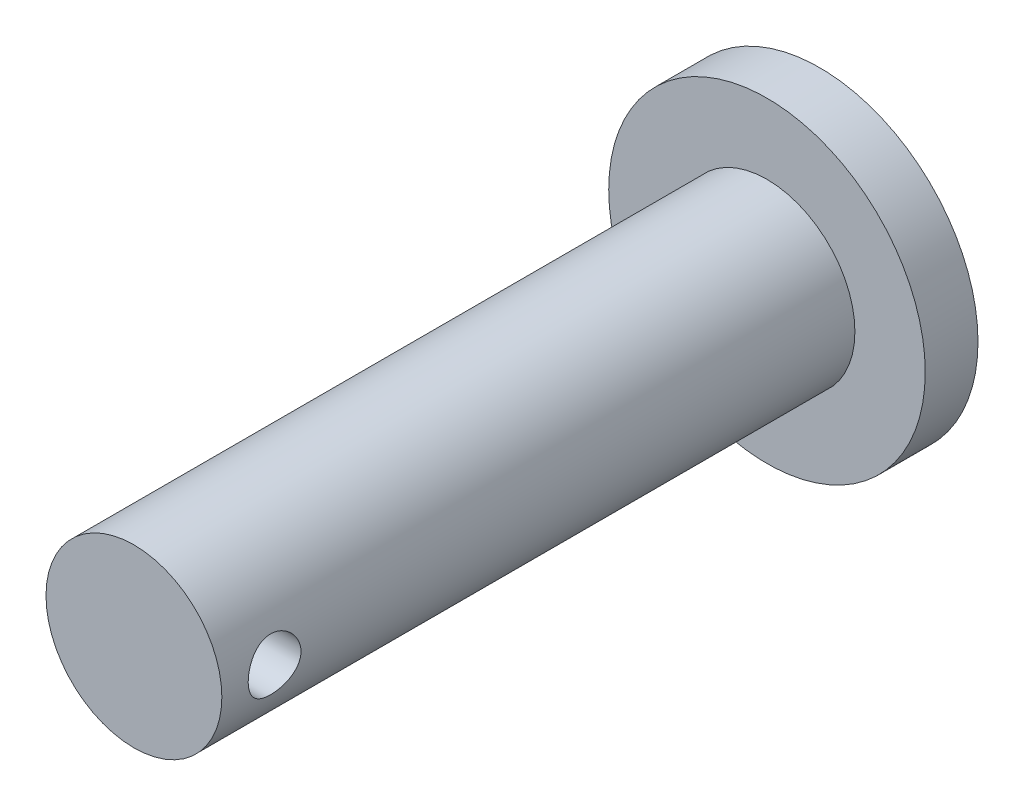
SolidWorks part; units mm, degrees
ref_plane "Front Plane" through (0, 0, 0) normal (0, 0, 1) x (1, 0, 0)
ref_plane "Top Plane" through (0, 0, 0) normal (0, 1, 0) x (1, 0, 0)
ref_plane "Right Plane" through (0, 0, 0) normal (1, 0, 0) x (0, 0, -1)
sketch "Sketch1" plane through (0, 0, 0) normal (0, 0, 1) x (1, 0, 0)
  circle A0 centre (0, 0) radius 5
  dimension "D1" = 10
extrude "Boss-Extrude1" add sketch "Sketch1" along normal blind 36
sketch "Sketch2" plane through (0, 0, 0) normal (0, 0, 1) x (1, 0, 0)
  circle A0 centre (0, 0) radius 9
  dimension "D1" = 18
extrude "Boss-Extrude2" add sketch "Sketch2" against normal blind 3
sketch "Sketch3" plane through (0, 0, 0) normal (1, 0, 0) x (0, 0, -1)
  line L0 (-36.7233, 0) -> (6.8823, 0) construction
  circle A0 centre (-33, 0) radius 1.5
  dimension "D1" = 3
  dimension "D2" = 33
extrude "Cut-Extrude1" cut sketch "Sketch3" against normal through all both and the other way through all
